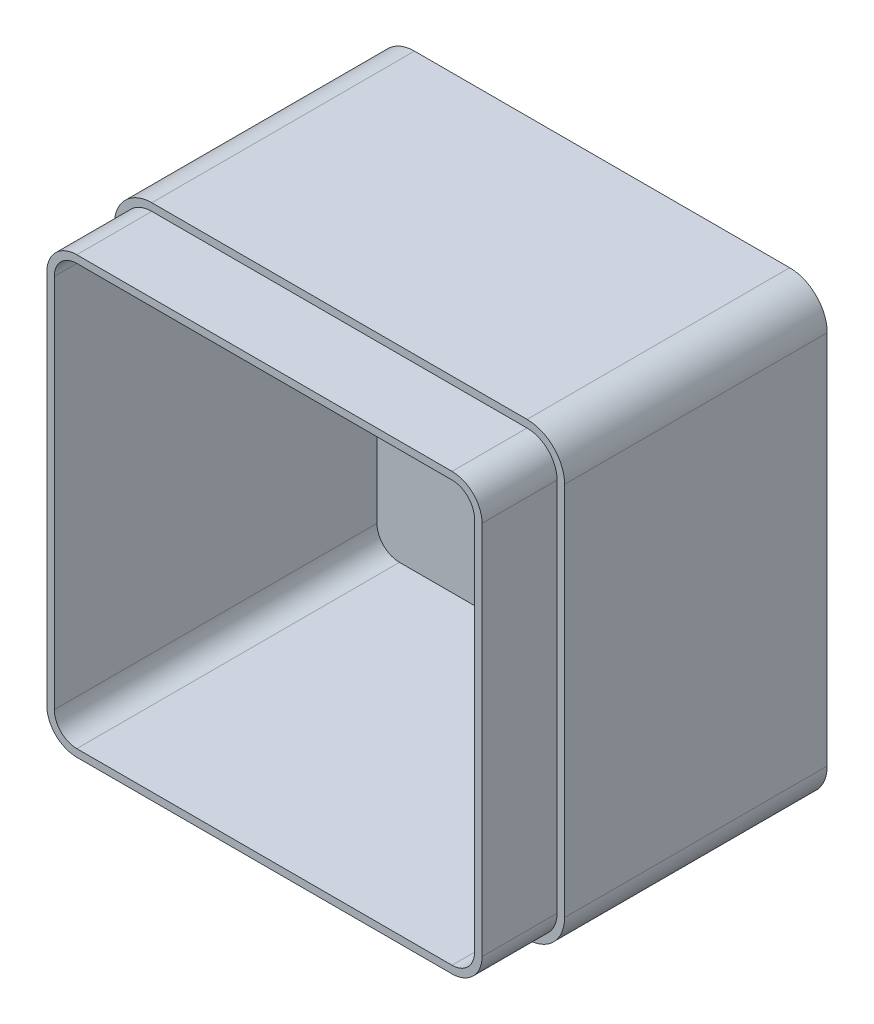
SolidWorks part; units mm, degrees
ref_plane "Front Plane" through (0, 0, 0) normal (0, 0, 1) x (1, 0, 0)
ref_plane "Top Plane" through (0, 0, 0) normal (0, 1, 0) x (1, 0, 0)
ref_plane "Right Plane" through (0, 0, 0) normal (1, 0, 0) x (0, 0, -1)
sketch "Sketch1" plane through (0, 0, 0) normal (0, 0, 1) x (1, 0, 0)
  line L1 (0, 0) -> (120, 0)
  line L2 (0, 0) -> (0, 120)
  line L3 (0, 120) -> (120, 120)
  line L4 (120, 0) -> (120, 120)
  dimension "D1" = 120
extrude "Boss-Extrude1" add sketch "Sketch1" along normal blind 90
fillet "Fillet1" radius 10 4 edges at (0, 0, 45) (0, 120, 45) (120, 0, 45) (120, 120, 45)
shell "Shell1" thickness 4
sketch "Sketch3" plane through (0, 0, 90) normal (0, 0, 1) x (1, 0, 0)
  line L0 (2, 110) -> (2, 10)
  line L1 (10, 2) -> (110, 2)
  line L2 (118, 10) -> (118, 110)
  line L3 (110, 118) -> (10, 118)
  line L4 (0, 110) -> (0, 10)
  line L5 (10, 0) -> (110, 0)
  line L6 (120, 10) -> (120, 110)
  line L7 (110, 120) -> (10, 120)
  line L8 (0, 110) -> (0, 10)
  line L9 (10, 0) -> (110, 0)
  line L10 (120, 10) -> (120, 110)
  line L11 (110, 120) -> (10, 120)
  arc A0 (2, 10) -> (10, 2) centre (10, 10) ccw
  arc A1 (110, 2) -> (118, 10) centre (110, 10) ccw
  arc A2 (118, 110) -> (110, 118) centre (110, 110) ccw
  arc A3 (10, 118) -> (2, 110) centre (10, 110) ccw
  arc A4 (0, 10) -> (10, 0) centre (10, 10) ccw
  arc A5 (110, 0) -> (120, 10) centre (110, 10) ccw
  arc A6 (120, 110) -> (110, 120) centre (110, 110) ccw
  arc A7 (10, 120) -> (0, 110) centre (10, 110) ccw
  arc A8 (0, 10) -> (10, 0) centre (10, 10) ccw
  arc A9 (110, 0) -> (120, 10) centre (110, 10) ccw
  arc A10 (120, 110) -> (110, 120) centre (110, 110) ccw
  arc A11 (10, 120) -> (0, 110) centre (10, 110) ccw
  dimension "D1" = 0
  dimension "D2" = 2
extrude "Cut-Extrude1" cut sketch "Sketch3" against normal blind 20
